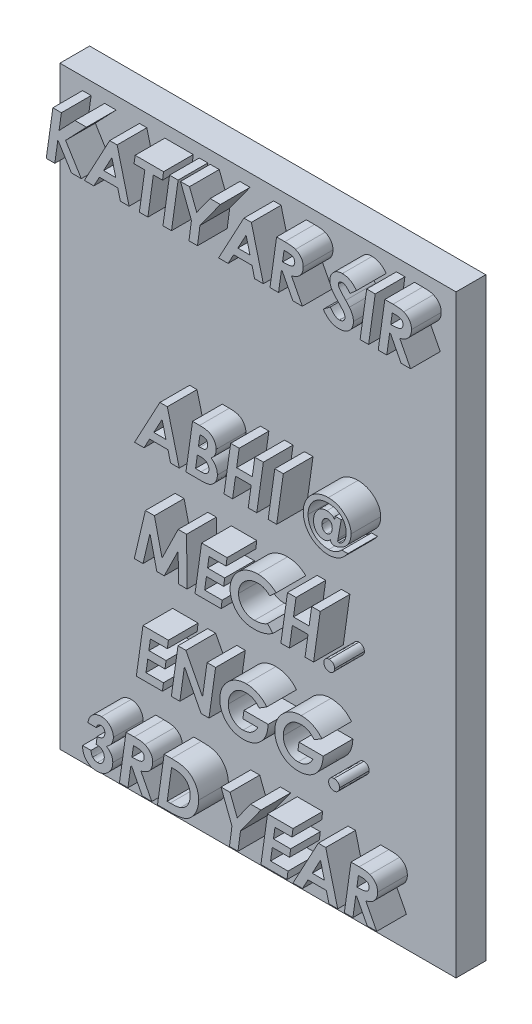
SolidWorks part; units mm, degrees
ref_plane "Front Plane" through (0, 0, 0) normal (0, 0, 1) x (1, 0, 0)
ref_plane "Top Plane" through (0, 0, 0) normal (0, 1, 0) x (1, 0, 0)
ref_plane "Right Plane" through (0, 0, 0) normal (1, 0, 0) x (0, 0, -1)
sketch "Sketch1" plane through (0, 0, 0) normal (0, 0, 1) x (1, 0, 0)
  line L1 (-10, -15) -> (10, -15)
  line L2 (-10, -15) -> (-10, 15)
  line L3 (-10, 15) -> (10, 15)
  line L4 (10, -15) -> (10, 15)
  line L5 (-10, -15) -> (10, 15) construction
  line L6 (-10, 15) -> (10, -15) construction
  point P0 (0, 0)
  dimension "D1" = 20
  dimension "D2" = 30
extrude "Boss-Extrude2" add sketch "Sketch1" along normal blind 1.5
sketch "Sketch3" plane through (0, 0, 1.5) normal (0, 0, 1) x (1, 0, 0)
  text T0 "KATIYAR SIR\r\n    \r\n     ABHI @\r\n     MECH.\r\n     ENGG.\r\n  3RD YEAR" font "Century Gothic" height in points 9
extrude "Boss-Extrude3" add sketch "Sketch3" along normal blind 1.5
